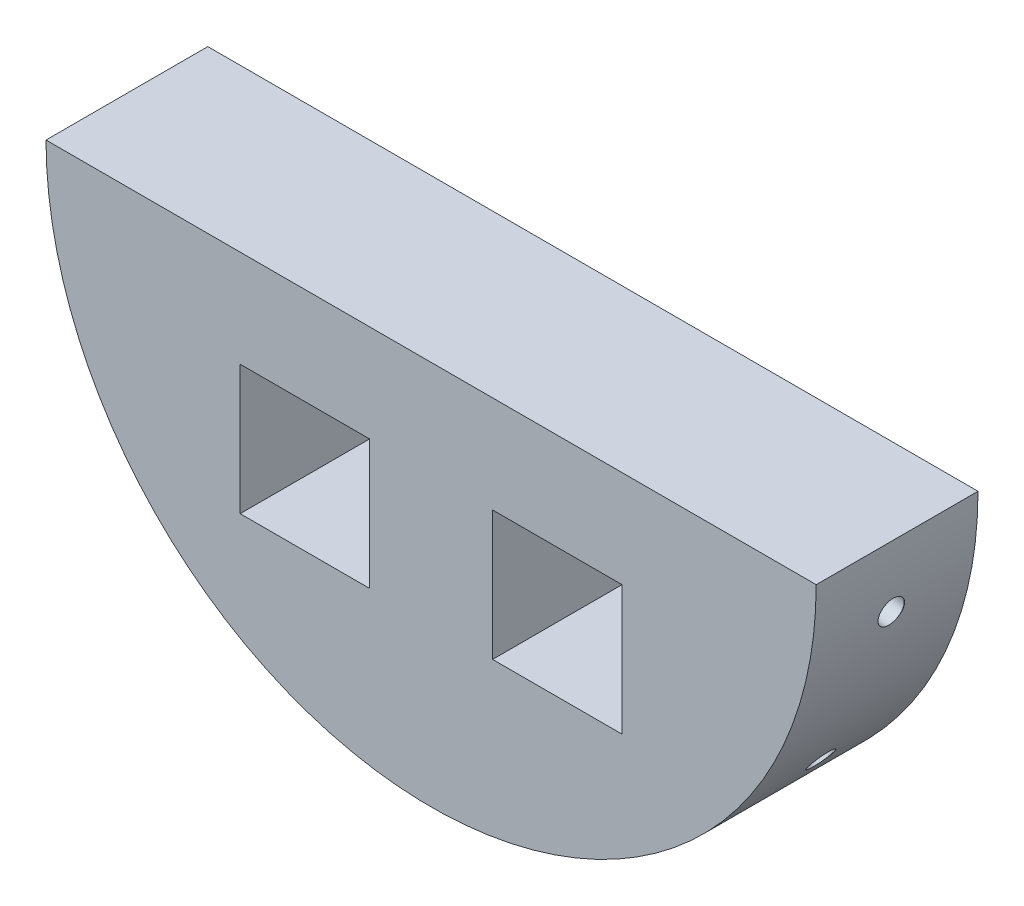
SolidWorks part; units mm, degrees
ref_plane "Front Plane" through (0, 0, 0) normal (0, 0, 1) x (1, 0, 0)
ref_plane "Top Plane" through (0, 0, 0) normal (0, 1, 0) x (1, 0, 0)
ref_plane "Right Plane" through (0, 0, 0) normal (1, 0, 0) x (0, 0, -1)
sketch "Sketch1" plane through (0, 0, 0) normal (0, 0, 1) x (1, 0, 0)
  line L0 (-119, 0) -> (0, 0)
  line L3 (-50, -35) -> (-30, -35)
  line L4 (-50, -35) -> (-50, -15)
  line L5 (-50, -15) -> (-30, -15)
  line L6 (-30, -35) -> (-30, -15)
  line L7 (-89, -35) -> (-69, -35)
  line L8 (-89, -35) -> (-89, -15)
  line L9 (-89, -15) -> (-69, -15)
  line L10 (-69, -35) -> (-69, -15)
  arc A1 (-119, 0) -> (0, 0) centre (-59.5, 0) ccw
  dimension "D1" = 30
  dimension "D7" = 59.5
  dimension "D2" = 15
  dimension "D3" = 30
  dimension "D4" = 20
extrude "Boss-Extrude1" add sketch "Sketch1" along normal blind 25
hole_wizard "Ø4.0mm Dowel Hole2" positions "3DSketch2" profile "Sketch4" hole size "Ø4.0" standard "ANSI Metric"
sketch3d "3DSketch2"
  line L2 (0, 0, 25) -> (0, 0, 0) construction
  line L4 (0, 0, 25) -> (0, 0, 0) construction
  line L5 (0, 0, 12.5) -> (-0.9039, -10.3321, 12.5) construction
  line L8 (-59.5, 0, 0) -> (-59.5, 0, 25) construction
  line L9 (0, 0, 0) -> (-119, 0, 0) construction
  line L10 (0, 0, 25) -> (-119, 0, 25) construction
  line L12 (-59.5, 0, 12.5) -> (-0.9039, -10.3321, 12.5) construction
  line L16 (-59.5, 0, 12.5) -> (0, 0, 12.5) construction
  point P0 (-0.9039, -10.3321, 12.5)
  point P16 (-0.9039, -10.3321, 12.5)
  point P23 (-0.9039, -10.3321, 12.5)
  point P25 (-0.9039, -10.3321, 12.5)
  dimension "D1" = 10
sketch "Sketch4" plane through (-0.9039, -10.3321, 12.5) normal (0, 0, 1) x (0.1736, 0.9848, 0)
  line L0 (0, 0) -> (0, 11.2017)
  line L1 (0, 11.2017) -> (2, 10)
  line L2 (2, 10) -> (2, 0.025)
  line L3 (2, 0.025) -> (2.025, 0)
  line L5 (2.025, 0) -> (0, 0)
  line L6 (-2, 0.025) -> (-2.025, 0) construction
  line L10 (0, 11.2017) -> (-2, 10) construction
  line L11 (0, -6.35) -> (0, 107.95) construction
  dimension "Hole Dia." = 4
  dimension "Hole Depth" = 10
  dimension "Near C'Sink Dia." = 4.05
  dimension "Near C'Sink Angle" = 90
  dimension "Drill Angle" = 118
pattern_circular "CirPattern1" count 7 over 160 about axis through (-59.5, 0, 0) along (0, 0, 1) of "Ø4.0mm Dowel Hole2"
